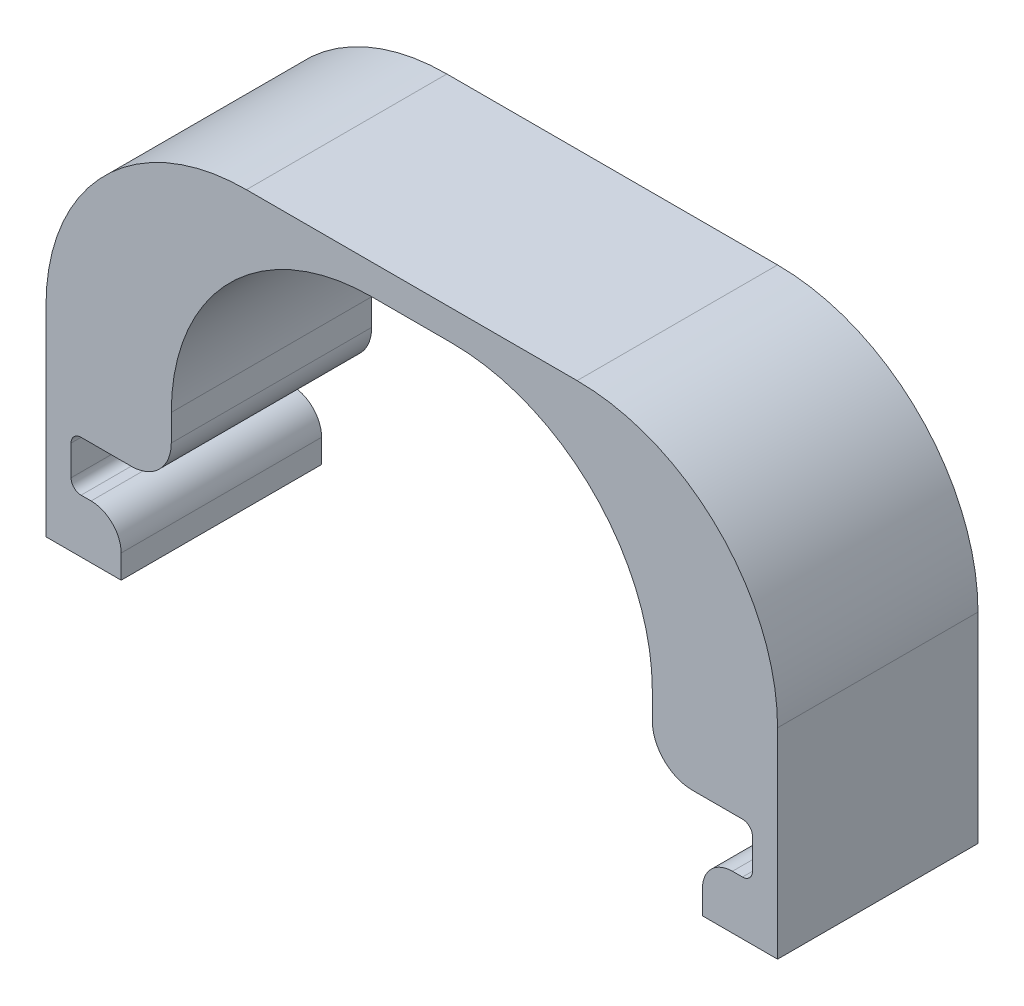
SolidWorks part; units mm, degrees
ref_plane "Front Plane" through (0, 0, 0) normal (0, 0, 1) x (1, 0, 0)
ref_plane "Top Plane" through (0, 0, 0) normal (0, 1, 0) x (1, 0, 0)
ref_plane "Right Plane" through (0, 0, 0) normal (1, 0, 0) x (0, 0, -1)
sketch "Sketch1" plane through (0, 0, 0) normal (0, 1, 0) x (1, 0, 0)
  line L1 (36.5, -10) -> (-36.5, -10)
  line L2 (36.5, -10) -> (36.5, 10)
  line L3 (36.5, 10) -> (-36.5, 10)
  line L4 (-36.5, -10) -> (-36.5, 10)
  line L5 (36.5, -10) -> (-36.5, 10) construction
  line L6 (36.5, 10) -> (-36.5, -10) construction
  point P0 (0, 0)
  dimension "D1" = 73
  dimension "D2" = 20
extrude "Boss-Extrude1" add sketch "Sketch1" along normal blind 40
sketch "Sketch2" plane through (0, 0, 10) normal (0, 0, 1) x (1, 0, 0)
  line L0 (-29, 0) -> (-29, 2.3524)
  line L1 (-36.5, 0) -> (36.5, 0) construction
  line L2 (-32, 5.3524) -> (-33, 5.3524)
  line L3 (-34, 6.3524) -> (-34, 9.3524)
  line L4 (-33, 10.3524) -> (-31, 10.3524)
  line L5 (-31, 10.3524) -> (-28, 10.3524)
  line L6 (-24, 14.3524) -> (-24, 37)
  line L7 (-24, 37) -> (24, 37)
  line L8 (-36.5, 40) -> (36.5, 40) construction
  line L9 (0, 40) -> (0, 0) construction
  line L10 (24, 14.3524) -> (24, 37)
  line L11 (31, 10.3524) -> (28, 10.3524)
  line L12 (33, 10.3524) -> (31, 10.3524)
  line L13 (34, 6.3524) -> (34, 9.3524)
  line L14 (32, 5.3524) -> (33, 5.3524)
  line L15 (29, 0) -> (29, 2.3524)
  line L16 (-29, 0) -> (29, 0)
  arc A0 (-34, 9.3524) -> (-33, 10.3524) centre (-33, 9.3524) cw
  arc A1 (-33, 5.3524) -> (-34, 6.3524) centre (-33, 6.3524) cw
  arc A2 (-29, 2.3524) -> (-32, 5.3524) centre (-32, 2.3524) ccw
  arc A3 (-28, 10.3524) -> (-24, 14.3524) centre (-28, 14.3524) ccw
  arc A4 (28, 10.3524) -> (24, 14.3524) centre (28, 14.3524) cw
  arc A5 (33, 5.3524) -> (34, 6.3524) centre (33, 6.3524) ccw
  arc A6 (34, 9.3524) -> (33, 10.3524) centre (33, 9.3524) ccw
  arc A7 (29, 2.3524) -> (32, 5.3524) centre (32, 2.3524) cw
  point P17 (-34, 10.3524)
  point P20 (-34, 5.3524)
  point P23 (-29, 5.3524)
  point P26 (-24, 10.3524)
  point P39 (0, 37)
  point P41 (24, 10.3524)
  point P42 (29, 5.3524)
  point P43 (34, 5.3524)
  point P44 (34, 10.3524)
  dimension "D6" = 1
  dimension "D7" = 3
  dimension "D10" = 4
  dimension "D1" = 5
  dimension "D2" = 3
  dimension "D3" = 34
  dimension "D4" = 5
  dimension "D5" = 10
  dimension "D8" = 5.3524
  dimension "D9" = 7
extrude "Cut-Extrude1" cut sketch "Sketch2" against normal blind 20
fillet "Fillet1" radius 20 2 edges at (36.5, 40, 0) (-36.5, 40, 0)
fillet "Fillet2" radius 20 2 edges at (24, 37, 0) (-24, 37, 0)
